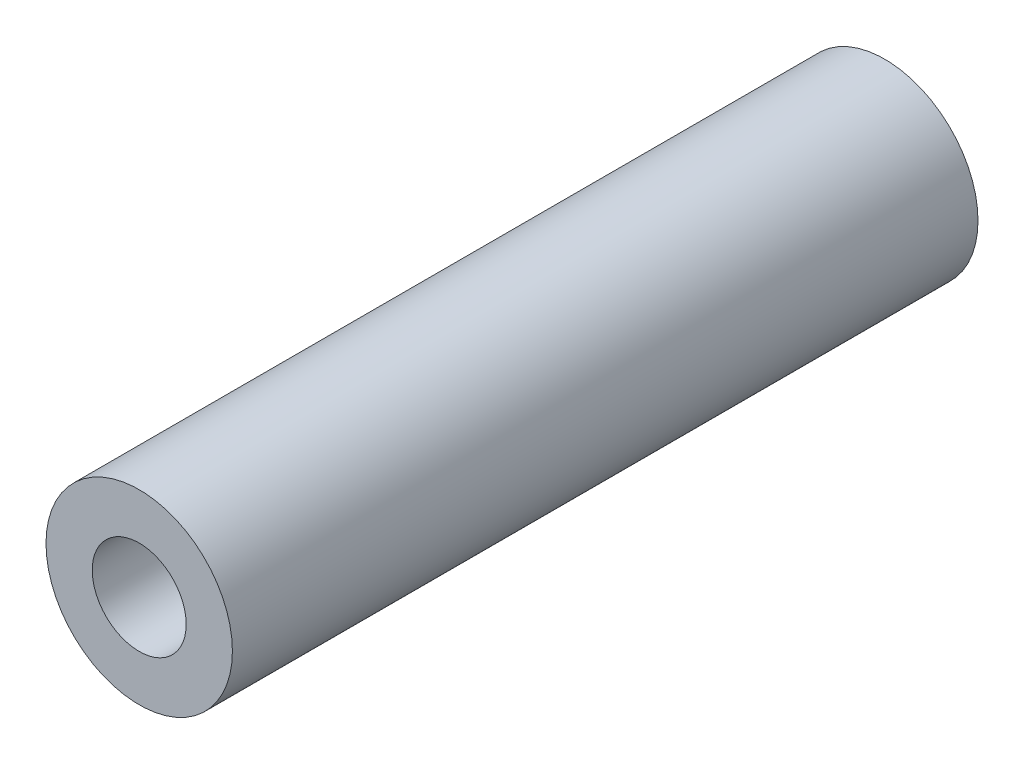
SolidWorks part; units mm, degrees
ref_plane "Front Plane" through (0, 0, 0) normal (0, 0, 1) x (1, 0, 0)
ref_plane "Top Plane" through (0, 0, 0) normal (0, 1, 0) x (1, 0, 0)
ref_plane "Right Plane" through (0, 0, 0) normal (1, 0, 0) x (0, 0, -1)
sketch "Sketch1" plane through (0, 0, 0) normal (0, 0, 1) x (1, 0, 0)
  circle A0 centre (0, 0) radius 6.35
  circle A1 centre (0, 0) radius 3.2004
  dimension "OD" = 12.7
  dimension "ID" = 6.4008
extrude "Extrude1" add sketch "Sketch1" along normal mid plane 50.8
sketch "Sketch2" plane through (0, 0, 0) normal (1, 0, 0) x (0, 0, -1)
  line L0 (-25.4, -3.2004) -> (25.4, -3.2004) construction
  line L3 (25.4, 3.2004) -> (-25.4, 3.2004) construction
  line L5 (-25.4, -3.2004) -> (25.4, -3.2004)
  line L6 (25.4, 3.2004) -> (-25.4, 3.2004)
sketch "Sketch4" plane through (0, 0, 25.4) normal (0, 0, 1) x (1, 0, 0)
  line L0 (0, 0) -> (-2.263, 2.263)
  line L1 (0, -5.2388) -> (0, 5.2388) construction
  circle A0 centre (0, 0) radius 3.2004 construction
  dimension "D1" = 45
